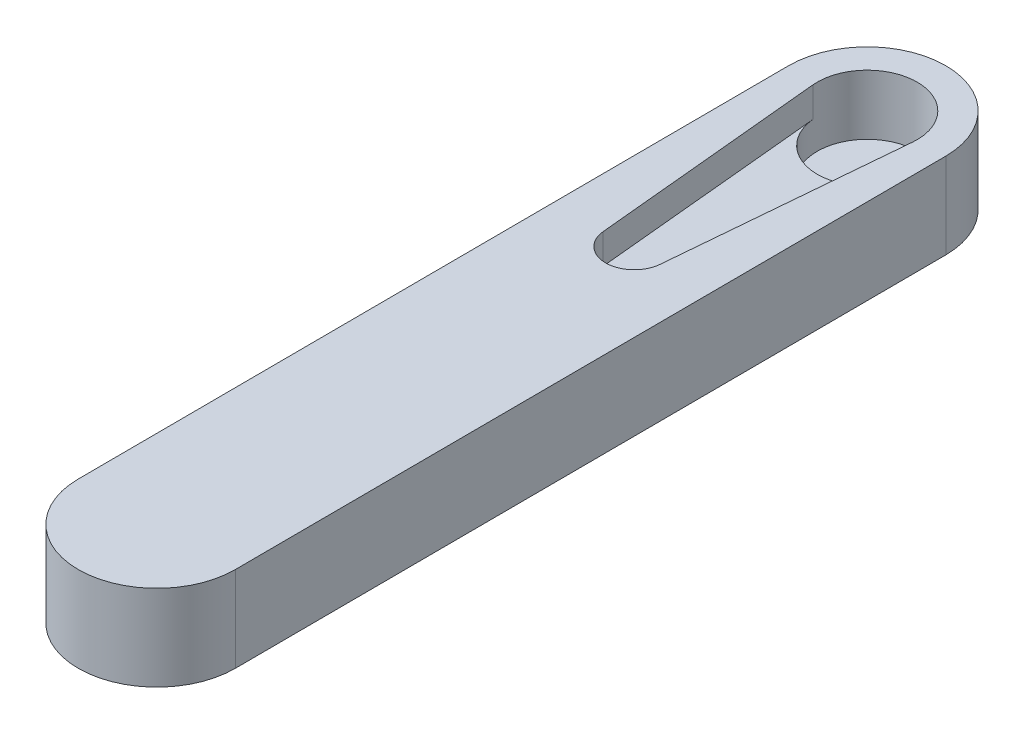
SolidWorks part; units mm, degrees
ref_plane "Спереди" through (0, 0, 0) normal (0, 0, 1) x (1, 0, 0)
ref_plane "Сверху" through (0, 0, 0) normal (0, 1, 0) x (1, 0, 0)
ref_plane "Справа" through (0, 0, 0) normal (1, 0, 0) x (0, 0, -1)
other "Configuration Table"
sketch "Эскиз2" plane through (0, 0, 0) normal (0, 1, 0) x (1, 0, 0)
  line L0 (-5.6963, 30.0104) -> (-5.4999, -19.9896)
  line L1 (5.3036, 30.0536) -> (5.5, -19.9464)
  arc A2 (-5.6963, 30.0104) -> (5.3036, 30.0536) centre (-0.1964, 30.032) cw
  arc A3 (-5.4999, -19.9896) -> (5.5, -19.9464) centre (0, -19.968) ccw
  dimension "D3" = 50
extrude "Бобышка-Вытянуть1" add sketch "Эскиз2" along normal blind 6
sketch "Эскиз3" plane through (0, 6, 0) normal (0, 1, 0) x (1, 0, 0)
  line L0 (-3.6804, 29.6982) -> (-2.1228, 13.4412)
  line L1 (3.2902, 29.7255) -> (1.8604, 13.4568)
  line L2 (5.5, -19.9464) -> (5.3036, 30.0536) construction
  arc A0 (-3.6804, 29.6982) -> (3.2902, 29.7255) centre (-0.1964, 30.032) cw
  arc A1 (-2.1228, 13.4412) -> (1.8604, 13.4568) centre (-0.132, 13.6319) ccw
  point P7 (-0.1241, 11.6319)
  point P8 (-0.2101, 33.5319)
  dimension "D1" = 3.5
  dimension "D2" = 2
  dimension "D3" = 21.9
  dimension "D4" = 5.5
extrude "Вырез-Вытянуть1" cut sketch "Эскиз3" against normal blind 2.1
sketch "Эскиз4" plane through (0, 3.9, 0) normal (0, 1, 0) x (1, 0, 0)
  circle A0 centre (-0.1964, 30.032) radius 3.5
extrude "Вырез-Вытянуть2" cut sketch "Эскиз4" against normal blind 2.1
